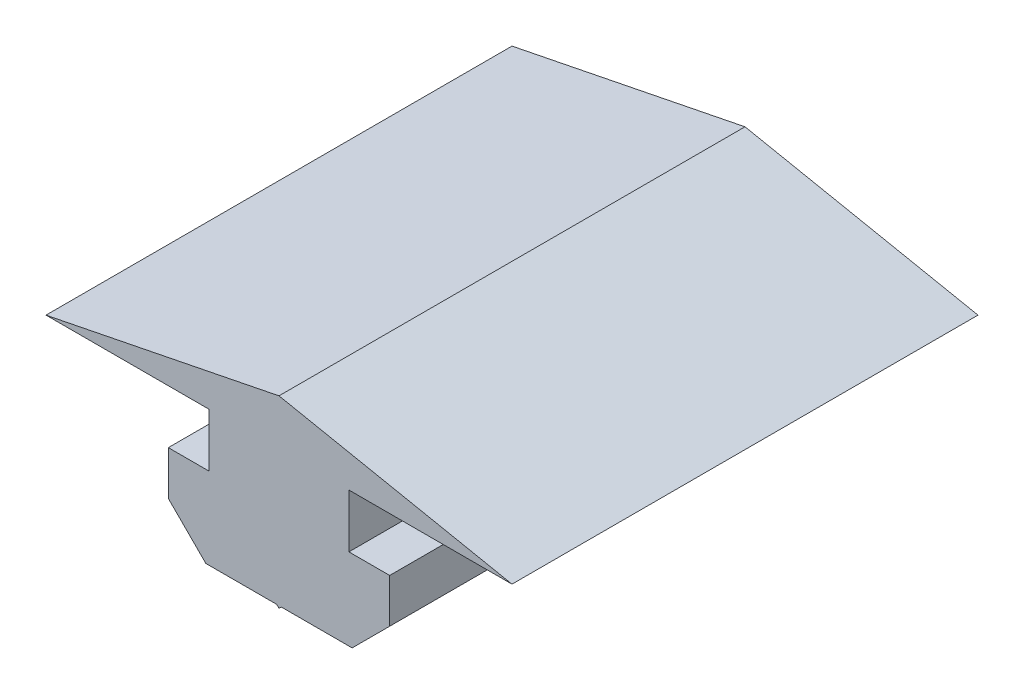
SolidWorks part; units mm, degrees
ref_plane "Front Plane" through (0, 0, 0) normal (0, 0, 1) x (1, 0, 0)
ref_plane "Top Plane" through (0, 0, 0) normal (0, 1, 0) x (1, 0, 0)
ref_plane "Right Plane" through (0, 0, 0) normal (1, 0, 0) x (0, 0, -1)
sketch "Sketch1" plane through (0, 0, 0) normal (0, 0, 1) x (1, 0, 0)
  line L0 (-10, 0) -> (10, 0)
  line L2 (-3, 0) -> (-4.75, 0)
  line L3 (-3, 0) -> (-3, -2.3)
  line L4 (-3, -2.3) -> (-4.75, -2.3)
  line L5 (-4.75, 0) -> (-4.75, -2.3)
  line L6 (3, 0) -> (3, -2.3)
  line L7 (0, 0) -> (0, 2)
  line L9 (-10, 0) -> (0, 2)
  line L11 (0, 2) -> (10, 0)
  line L12 (3, -2.3) -> (4.75, -2.3)
  point P2 (0, 0)
  line B0 (0, -10) -> (0, 0) construction
  line B1 (0, -5.9) -> (-0.1, -5.8)
  line B2 (-0.1, -5.8) -> (-3.1393, -5.8)
  line B3 (-3.1393, -5.8) -> (-4.75, -4.1893)
  line B4 (-4.75, -4.1893) -> (-4.75, -1.8)
  line B5 (-4.75, -1.8) -> (-3, -1.8)
  line B6 (-3, -1.8) -> (-3, -1.75)
  line B7 (-3, -1.75) -> (-4.75, 0)
  line B8 (-4.75, 0) -> (4.75, 0)
  line B9 (0, -10) -> (-5.9927, -4.0073) construction
  line B10 (3, -1.75) -> (4.75, 0)
  line B11 (3, -1.8) -> (3, -1.75)
  line B12 (4.75, -1.8) -> (3, -1.8)
  line B13 (4.75, -4.1893) -> (4.75, -1.8)
  line B14 (3.1393, -5.8) -> (4.75, -4.1893)
  line B15 (0.1, -5.8) -> (3.1393, -5.8)
  line B16 (0, -5.9) -> (0.1, -5.8)
  dimension "D1" = 20
  dimension "D2" = 2
sketch_block_instance "V Slot 1-12"
sketch_block "V Slot 1" parameters "D1"=10, "D2"=9.5, "D3"=4, "D4"=1.8, "D5"=0.1, "D6"=45, "D7"=9.5, "D8"=1.5, "D9"=6, "D10"=2.6393
extrude "Boss-Extrude1" add sketch "Sketch1" along normal blind 20 contours L9 L0 L7 | B1 B16 B15 B14 B13 L12 L6 L0 L3 L4 B4 B3 B2 | L11 L7 L0
